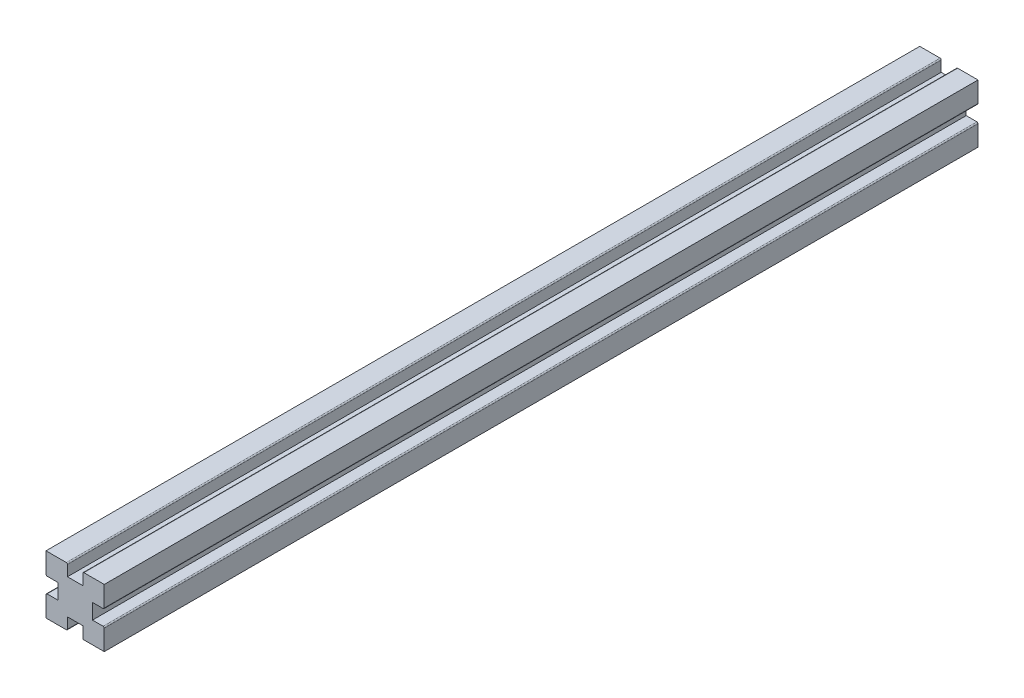
SolidWorks part; units mm, degrees
ref_plane "Front Plane" through (0, 0, 0) normal (0, 0, 1) x (1, 0, 0)
ref_plane "Top Plane" through (0, 0, 0) normal (0, 1, 0) x (1, 0, 0)
ref_plane "Right Plane" through (0, 0, 0) normal (1, 0, 0) x (0, 0, -1)
sketch "Sketch1" plane through (0, 0, 0) normal (0, 0, 1) x (1, 0, 0)
  line L0 (12.7, 3.34) -> (7.5682, 3.34)
  line L1 (-12.7, 12.7) -> (12.7, 12.7)
  line L2 (-12.7, 12.7) -> (-12.7, -12.7)
  line L3 (-12.7, -12.7) -> (12.7, -12.7)
  line L4 (12.7, 12.7) -> (12.7, -12.7)
  line L5 (-3.34, 12.7) -> (3.34, 12.7)
  line L6 (-3.34, 12.7) -> (-3.34, 7.5682)
  line L7 (-3.34, 7.5682) -> (3.34, 7.5682)
  line L8 (3.34, 12.7) -> (3.34, 7.5682)
  line L9 (12.7, 3.34) -> (12.7, -3.34)
  line L10 (12.7, -3.34) -> (7.5682, -3.34)
  line L11 (7.5682, 3.34) -> (7.5682, -3.34)
  line L12 (3.34, -12.7) -> (3.34, -7.5682)
  line L13 (3.34, -12.7) -> (-3.34, -12.7)
  line L14 (-3.34, -12.7) -> (-3.34, -7.5682)
  line L15 (3.34, -7.5682) -> (-3.34, -7.5682)
  line L16 (-12.7, -3.34) -> (-7.5682, -3.34)
  line L17 (-12.7, -3.34) -> (-12.7, 3.34)
  line L18 (-12.7, 3.34) -> (-7.5682, 3.34)
  line L19 (-7.5682, -3.34) -> (-7.5682, 3.34)
  circle A0 centre (0, 0) radius 12.7 construction
  point P4 (0, 12.7)
  point P6 (-12.7, 0)
  point P11 (0, 7.5682)
  point P29 (0, 0)
  dimension "D1" = 25.4
  dimension "D2" = 5.1318
  dimension "D3" = 6.68
  dimension "D4" = 4
extrude "Boss-Extrude1" add sketch "Sketch1" along normal blind 381 contours L19 L16 L2 L3 L14 L15 L12 L4 L10 L11 L0 L1 L8 L7 L6 L18
fillet "Fillet1" radius 0.5 8 edges at (-3.34, -12.7, 190.5) (3.34, -12.7, 190.5) (-12.7, -3.34, 190.5) (-12.7, 3.34, 190.5) (12.7, 3.34, 190.5) (12.7, -3.34, 190.5) (-3.34, 12.7, 190.5) (3.34, 12.7, 190.5)
